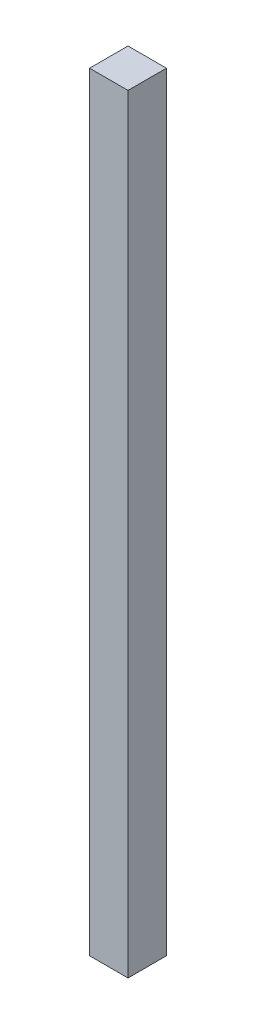
SolidWorks part; units mm, degrees
ref_plane "Front Plane" through (0, 0, 0) normal (0, 0, 1) x (1, 0, 0)
ref_plane "Top Plane" through (0, 0, 0) normal (0, 1, 0) x (1, 0, 0)
ref_plane "Right Plane" through (0, 0, 0) normal (1, 0, 0) x (0, 0, -1)
sketch "Sketch1" plane through (0, 0, 0) normal (0, 1, 0) x (1, 0, 0)
  line L1 (0, 0) -> (2, 0)
  line L2 (0, 0) -> (0, -2)
  line L3 (0, -2) -> (2, -2)
  line L4 (2, 0) -> (2, -2)
  line L5 (0, 0) -> (2, -2) construction
  line L6 (0, -2) -> (2, 0) construction
  circle A0 centre (1, -1) radius 1 construction
  point P2 (0, -1)
  point P3 (1, 0)
  dimension "D1" = 2
extrude "Boss-Extrude1" add sketch "Sketch1" along normal blind 40
